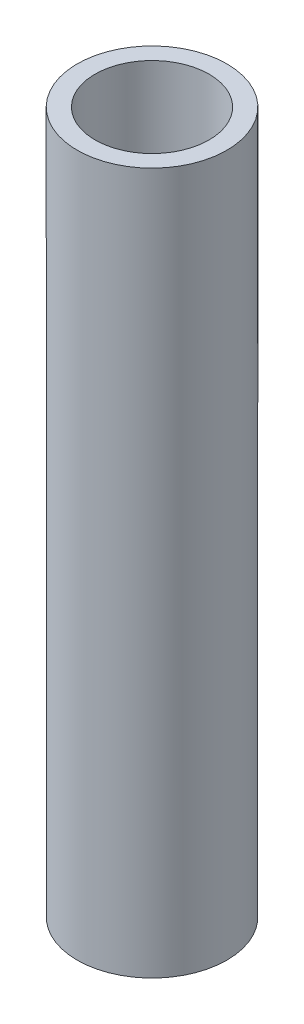
SolidWorks part; units mm, degrees
material "AISI 316 Stainless Steel Sheet (SS)"
ref_plane "Front Plane" through (0, 0, 0) normal (0, 0, 1) x (1, 0, 0)
ref_plane "Top Plane" through (0, 0, 0) normal (0, 1, 0) x (1, 0, 0)
ref_plane "Right Plane" through (0, 0, 0) normal (1, 0, 0) x (0, 0, -1)
sketch "Sketch1" plane through (0, 0, 0) normal (0, 1, 0) x (1, 0, 0)
  circle A0 centre (0, 0) radius 1.05
  circle A1 centre (0, 0) radius 0.8
  dimension "D1" = 2.1
  dimension "D2" = 1.6
extrude "Boss-Extrude1" add sketch "Sketch1" along normal offset from surface (9.841 mm away) 5 contours A1 | A0
